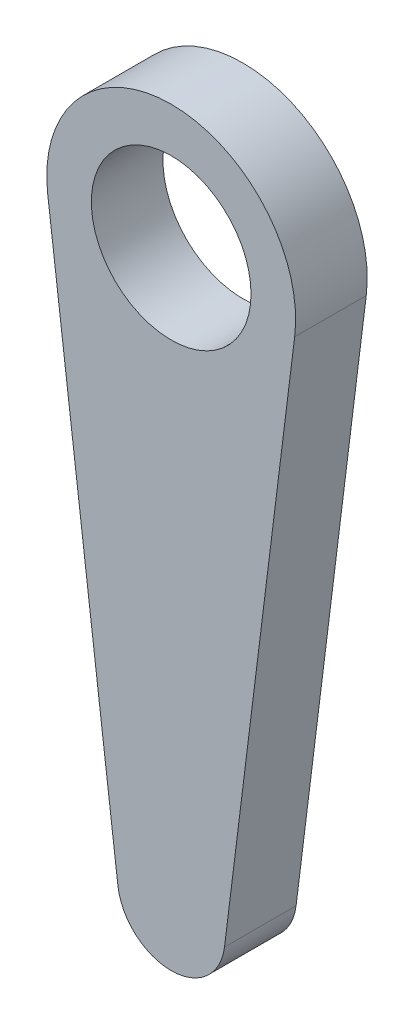
SolidWorks part; units mm, degrees
ref_plane "前视基准面" through (0, 0, 0) normal (0, 0, 1) x (1, 0, 0)
ref_plane "上视基准面" through (0, 0, 0) normal (0, 1, 0) x (1, 0, 0)
ref_plane "右视基准面" through (0, 0, 0) normal (1, 0, 0) x (0, 0, -1)
sketch "草图1" plane through (0, 0, 0) normal (0, 0, 1) x (1, 0, 0)
  line L0 (0, 3.475) -> (0, -15.985)
  line L1 (3.4484, -0.4293) -> (1.8579, -13.2035)
  line L2 (1.8579, -13.2035) -> (1.4885, -16.1703)
  line L3 (-1.8579, -13.2035) -> (-1.4885, -16.1703)
  line L4 (-3.4484, -0.4293) -> (-1.8579, -13.2035)
  circle A0 centre (0, 0) radius 3.475
  circle A1 centre (0, 0) radius 2.23
  circle A2 centre (0, -15.985) radius 1.5
  dimension "D1" = 6.95
  dimension "D2" = 4.46
  dimension "D4" = 3
  dimension "D3" = 19.46
extrude "凸台-拉伸1" add sketch "草图1" along normal blind 2
sketch "草图2" plane through (0, 0, 2) normal (0, 0, 1) x (1, 0, 0)
  circle A0 centre (0, 0) radius 3.475
  dimension "D1" = 6.95
sketch "草图3" plane through (0, 0, 2) normal (0, 0, 1) x (1, 0, 0)
  line L0 (0, 0) -> (0, -17.485)
  circle A1 centre (0, 0) radius 3.475
  arc A2 (-1.4885, -16.1703) -> (1.4885, -16.1703) centre (0, -15.985) ccw construction
